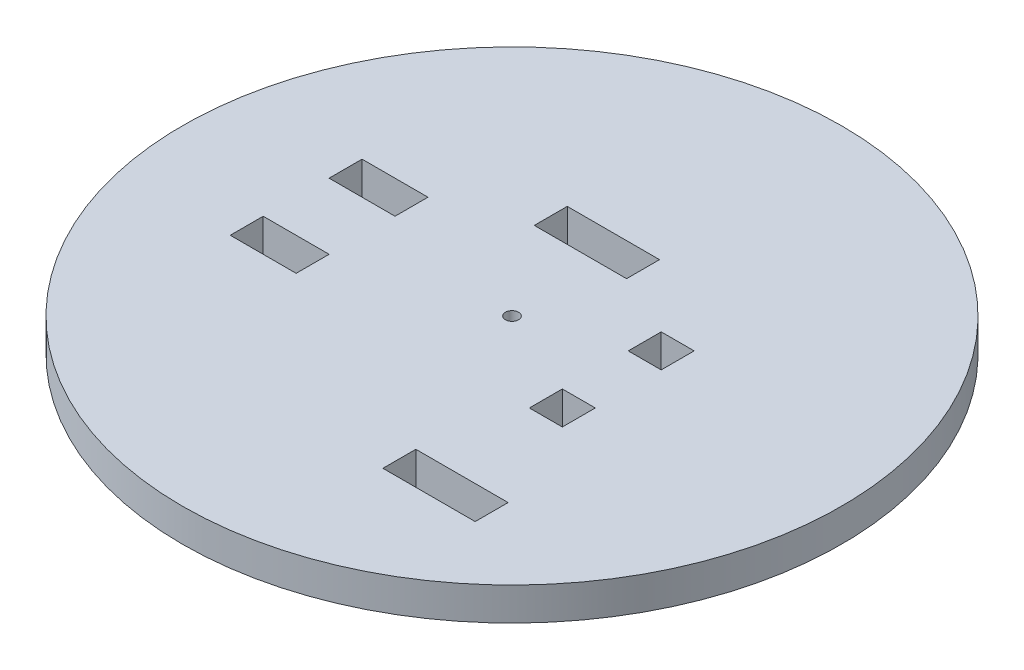
SolidWorks part; units mm, degrees
ref_plane "Front Plane" through (0, 0, 0) normal (0, 0, 1) x (1, 0, 0)
ref_plane "Top Plane" through (0, 0, 0) normal (0, 1, 0) x (1, 0, 0)
ref_plane "Right Plane" through (0, 0, 0) normal (1, 0, 0) x (0, 0, -1)
sketch "Sketch1" plane through (0, 0, 0) normal (0, 1, 0) x (1, 0, 0)
  line L0 (0, 0) -> (63.5, 0) construction
  line L1 (63.5, 0) -> (-63.5, 0) construction
  line L2 (-34.2628, 5.3734) -> (-34.2628, 11.7234)
  line L3 (17.0255, -7.3266) -> (23.3755, -7.3266)
  line L4 (-27.9128, -7.3266) -> (-27.9128, -13.6766)
  line L5 (17.0255, 5.3734) -> (17.0255, 11.7234)
  line L6 (23.3755, 5.3734) -> (17.0255, 5.3734)
  line L7 (17.0255, -13.6766) -> (-27.9128, -13.6766) construction
  line L8 (23.3755, -13.6766) -> (17.0255, -13.6766)
  line L9 (-27.9128, -13.6766) -> (-27.6523, -13.7288)
  line L10 (23.3755, 11.7234) -> (17.0255, 11.7234)
  line L11 (17.0255, -13.6766) -> (17.0255, -7.3266)
  line L12 (-5.4437, -13.6766) -> (-5.4437, 19.5691) construction
  line L13 (-34.2628, 5.3734) -> (-27.9128, 5.3734)
  line L14 (-34.2628, -13.6766) -> (-27.9128, -13.6766)
  line L15 (-27.9128, -7.3266) -> (-34.2628, -7.3266)
  line L16 (-27.9128, 5.3734) -> (-27.9128, 11.7234)
  line L17 (-34.2628, -13.6766) -> (-34.2628, -7.3266)
  line L18 (-34.2628, 11.7234) -> (-27.9128, 11.7234)
  line L19 (23.3755, 11.7234) -> (23.3755, 5.3734)
  line L20 (23.3755, -7.3266) -> (23.3755, -13.6766)
  line L21 (-34.2628, -13.6766) -> (-40.6128, -13.6766)
  line L22 (-12.9663, 23.6124) -> (4.8137, 23.6124)
  line L23 (-12.9663, 23.6124) -> (-12.9663, 17.2624)
  line L24 (-12.9663, 17.2624) -> (4.8137, 17.2624)
  line L25 (4.8137, 23.6124) -> (4.8137, 17.2624)
  line L26 (12.9806, -31.5072) -> (30.7606, -31.5072)
  line L27 (12.9806, -31.5072) -> (12.9806, -37.8572)
  line L28 (12.9806, -37.8572) -> (30.7606, -37.8572)
  line L29 (30.7606, -31.5072) -> (30.7606, -37.8572)
  line L30 (-40.6128, -13.6766) -> (-40.6128, -7.3266)
  line L31 (-40.6128, -7.3266) -> (-34.2628, -7.3266)
  line L32 (-34.2628, 5.3734) -> (-40.6128, 5.3734)
  line L33 (-40.6128, 5.3734) -> (-40.6128, 11.7234)
  line L34 (-40.6128, 11.7234) -> (-34.2628, 11.7234)
  circle A0 centre (0, 0) radius 63.5
  circle A1 centre (0, 0) radius 1.27
  dimension "D1" = 6.35
  dimension "D2" = 6.35
  dimension "D3" = 12.7
extrude "Boss-Extrude3" add sketch "Sketch1" along normal blind 6.35
